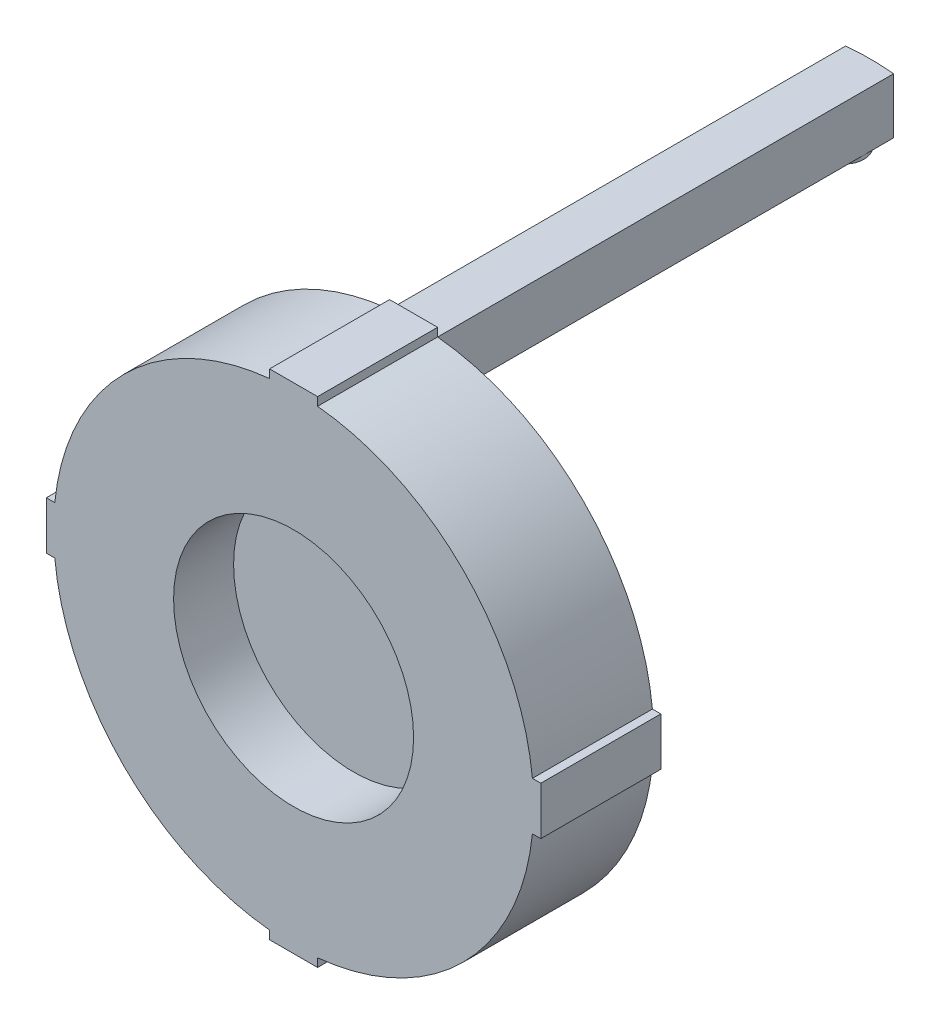
SolidWorks part; units mm, degrees
ref_plane "Ön Düzlem" through (0, 0, 0) normal (0, 0, 1) x (1, 0, 0)
ref_plane "Üst Düzlem" through (0, 0, 0) normal (0, 1, 0) x (1, 0, 0)
ref_plane "Sağ Düzlem" through (0, 0, 0) normal (1, 0, 0) x (0, 0, -1)
sketch "Sketch1" plane through (0, 0, 0) normal (0, 0, 1) x (1, 0, 0)
  circle A0 centre (0, 0) radius 5
  dimension "D1" = 10
extrude "Boss-Extrude1" add sketch "Sketch1" along normal blind 2.5
sketch "Sketch6" plane through (0, 0, 2.5) normal (0, 0, 1) x (1, 0, 0)
  line L1 (-5.15, 0.5) -> (-4.9, 0.5)
  line L2 (-5.15, 0.5) -> (-5.15, -0.5)
  line L3 (-5.15, -0.5) -> (-4.9, -0.5)
  line L4 (-4.9, 0.5) -> (-4.9, -0.5)
  point P4 (-4.9, 0)
  dimension "D1" = 0.25
  dimension "D2" = 1
  dimension "D3" = 4.9
extrude "Boss-Extrude4" add sketch "Sketch6" against normal blind 2.5
pattern_circular "CirPattern1" count 4 over 360 about axis through (0, 0, 0) along (0, 0, 1) of "Boss-Extrude4"
sketch "Sketch8" plane through (0, 0, 2.5) normal (0, 0, 1) x (1, 0, 0)
  circle A0 centre (0, 0) radius 2.5
  dimension "D1" = 5
extrude "Cut-Extrude3" cut sketch "Sketch8" against normal blind 1.25
sketch "Sketch9" plane through (0, 0, 0) normal (0, 0, -1) x (-1, 0, 0)
  line L0 (-0.5, 5.15) -> (0.5, 5.15) construction
  line L1 (-0.5, 5.15) -> (0.5, 5.15)
  line L2 (-0.5, 5.15) -> (-0.5, 3.8)
  line L3 (-0.5, 3.8) -> (0.5, 3.8)
  line L4 (0.5, 5.15) -> (0.5, 3.8)
  line L5 (0.5, 5.15) -> (0.5, 4.9749) construction
  line L6 (-0.5, 4.9749) -> (-0.5, 5.15) construction
  dimension "D1" = 3.8
extrude "Boss-Extrude5" add sketch "Sketch9" along normal blind 9.5
sketch "Sketch11" plane through (0, 0, 0) normal (0, 0, -1) x (-1, 0, 0)
  circle A0 centre (0, 0) radius 3.85
  dimension "D1" = 7.7
extrude "Cut-Extrude4" cut sketch "Sketch11" along normal blind 14
sketch "Sketch12" plane through (0, 5.15, 0) normal (0, 1, 0) x (1, 0, 0)
  line L0 (-0.5, 9.5) -> (0.5, 9.5) construction
  circle A0 centre (0, 8.9) radius 0.48
  dimension "D1" = 0.96
  dimension "D2" = 0.6
extrude "Boss-Extrude6" add sketch "Sketch12" against normal blind 7
sketch "Sketch13" plane through (0, 0, -9.5) normal (0, 0, -1) x (-1, 0, 0)
  circle A0 centre (0, 0) radius 3.75
  dimension "D1" = 7.5
extrude "Cut-Extrude5" cut sketch "Sketch13" against normal blind 7
sketch "Sketch14" plane through (0, 0, 0) normal (0, 0, -1) x (-1, 0, 0)
  circle A0 centre (0, 0) radius 5
  circle A1 centre (0, 0) radius 6.795
extrude "Cut-Extrude6" cut sketch "Sketch14" along normal blind 17
